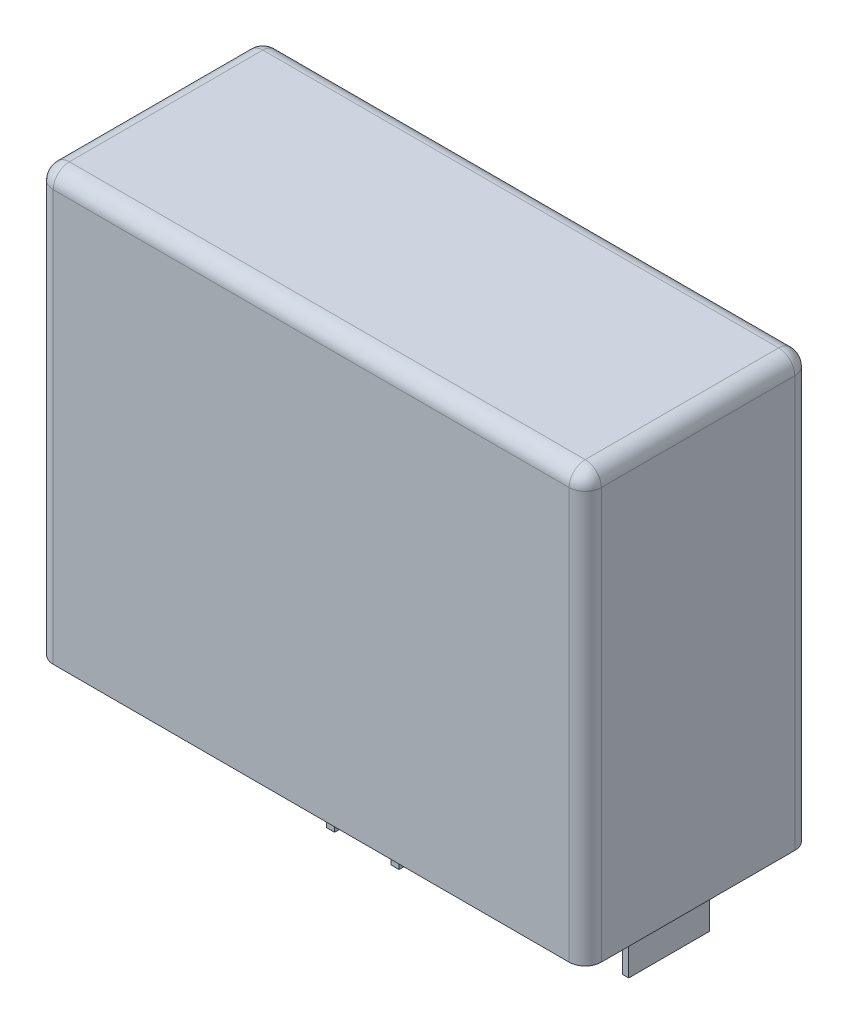
SolidWorks part; units mm, degrees
ref_plane "Front Plane" through (0, 0, 0) normal (0, 0, 1) x (1, 0, 0)
ref_plane "Top Plane" through (0, 0, 0) normal (0, 1, 0) x (1, 0, 0)
ref_plane "Right Plane" through (0, 0, 0) normal (1, 0, 0) x (0, 0, -1)
sketch "Sketch1" plane through (0, 0, 0) normal (0, 1, 0) x (1, 0, 0)
  line L1 (-16, -7) -> (16, -7)
  line L2 (-17, -6) -> (-17, 6)
  line L3 (-16, 7) -> (16, 7)
  line L4 (17, -6) -> (17, 6)
  line L5 (-17, -7) -> (17, 7) construction
  line L6 (-17, 7) -> (17, -7) construction
  arc A0 (16, 7) -> (17, 6) centre (16, 6) cw
  arc A1 (17, -6) -> (16, -7) centre (16, -6) cw
  arc A2 (-17, -6) -> (-16, -7) centre (-16, -6) ccw
  arc A3 (-17, 6) -> (-16, 7) centre (-16, 6) cw
  point P0 (0, 0)
  dimension "D3" = 1
  dimension "D1" = 34
  dimension "D2" = 14
extrude "Boss-Extrude1" add sketch "Sketch1" along normal blind 26.5
sketch "Sketch2" plane through (0, 0, 0) normal (0, -1, 0) x (1, 0, 0)
  line L0 (-2.5769, 0) -> (-6.5317, 0) construction
  line L1 (-15.2, -2.5) -> (-14.8, -2.5)
  line L2 (-15.2, -2.5) -> (-15.2, 2.5)
  line L3 (-15.2, 2.5) -> (-14.8, 2.5)
  line L4 (-14.8, -2.5) -> (-14.8, 2.5)
  line L5 (-15.2, -2.5) -> (-14.8, 2.5) construction
  line L6 (-15.2, 2.5) -> (-14.8, -2.5) construction
  line L7 (14.8, -2.5) -> (15.2, -2.5)
  line L8 (14.8, -2.5) -> (14.8, 2.5)
  line L9 (14.8, 2.5) -> (15.2, 2.5)
  line L10 (15.2, -2.5) -> (15.2, 2.5)
  line L11 (14.8, -2.5) -> (15.2, 2.5) construction
  line L12 (14.8, 2.5) -> (15.2, -2.5) construction
  line L14 (-1.75, 3.8) -> (-2.25, 3.8)
  line L15 (-1.75, 3.8) -> (-1.75, 2.8)
  line L16 (-1.75, 2.8) -> (-2.25, 2.8)
  line L17 (-2.25, 3.8) -> (-2.25, 2.8)
  line L18 (-1.75, 3.8) -> (-2.25, 2.8) construction
  line L19 (-1.75, 2.8) -> (-2.25, 3.8) construction
  line L20 (2.25, 3.8) -> (1.75, 3.8)
  line L21 (2.25, 3.8) -> (2.25, 2.8)
  line L22 (2.25, 2.8) -> (1.75, 2.8)
  line L23 (1.75, 3.8) -> (1.75, 2.8)
  line L24 (2.25, 3.8) -> (1.75, 2.8) construction
  line L25 (2.25, 2.8) -> (1.75, 3.8) construction
  point P0 (-15, 0)
  point P5 (15, 0)
  point P11 (2, 3.3)
  point P16 (-2, 3.3)
  dimension "D1" = 5
  dimension "D2" = 5
  dimension "D3" = 0.4
  dimension "D4" = 0.4
  dimension "D5" = 15
  dimension "D6" = 15
  dimension "D7" = 2
  dimension "D8" = 2
  dimension "D9" = 3.3
  dimension "D10" = 3.3
  dimension "D11" = 0.5
  dimension "D12" = 0.5
  dimension "D13" = 1
  dimension "D14" = 1
extrude "Boss-Extrude2" add sketch "Sketch2" along normal blind 3.5
fillet "Fillet1" radius 1 8 edges at (17, 26.5, 0) (16.7071, 26.5, 6.7071) (0, 26.5, 7) (-16.7071, 26.5, 6.7071) (-17, 26.5, 0) (-16.7071, 26.5, -6.7071) (0, 26.5, -7) (16.7071, 26.5, -6.7071)
